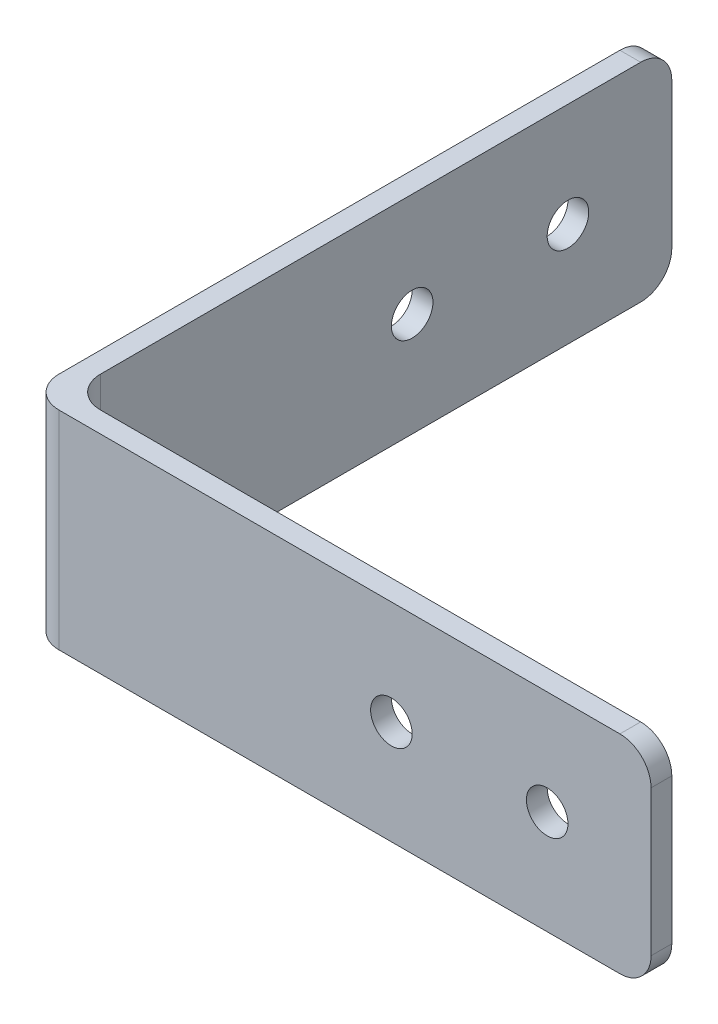
SolidWorks part; units mm, degrees
material "AISI 321 Annealed Stainless Steel (SS)"
ref_plane "Front Plane" through (0, 0, 0) normal (0, 0, 1) x (1, 0, 0)
ref_plane "Top Plane" through (0, 0, 0) normal (0, 1, 0) x (1, 0, 0)
ref_plane "Right Plane" through (0, 0, 0) normal (1, 0, 0) x (0, 0, -1)
sketch "Sketch1" plane through (0, 0, 0) normal (0, 1, 0) x (1, 0, 0)
  line L0 (-31.6449, 36.3551) -> (-31.6449, -21.6449)
  line L1 (-31.6449, -21.6449) -> (26.3551, -21.6449)
  line L2 (26.3551, -21.6449) -> (26.3551, -23.6449)
  line L3 (26.3551, -23.6449) -> (-33.6449, -23.6449)
  line L4 (-33.6449, -23.6449) -> (-33.6449, 36.3551)
  line L5 (-33.6449, 36.3551) -> (-31.6449, 36.3551)
  dimension "D1" = 60
  dimension "D2" = 60
  dimension "D3" = 58
  dimension "D4" = 58
  dimension "D5" = 2
extrude "Boss-Extrude1" add sketch "Sketch1" along normal blind 20
fillet "Fillet1" radius 3 6 edges at (-31.6449, 10, 21.6449) (-33.6449, 10, 23.6449) (26.3551, 20, 22.6449) (26.3551, 0, 22.6449) (-32.6449, 0, -36.3551) (-32.6449, 20, -36.3551)
sketch "Sketch3" plane through (0, 0, 21.6449) normal (0, 0, -1) x (-1, 0, 0)
  line L0 (-26.3551, 10) -> (28.6449, 10) construction
  line L1 (-26.3551, 17) -> (-26.3551, 3) construction
  line L2 (28.6449, 0) -> (28.6449, 20) construction
  circle A0 centre (-1.3551, 10) radius 2
  circle A1 centre (-16.3551, 10) radius 2
  dimension "D1" = 4
  dimension "D2" = 4
  dimension "D3" = 10
  dimension "D4" = 15
sketch "Sketch4" plane through (-31.6449, 0, 0) normal (1, 0, 0) x (0, 0, -1)
  line L0 (-18.6449, 10) -> (36.3551, 10) construction
  line L3 (36.3551, 17) -> (36.3551, 3) construction
  line L4 (-18.6449, 20) -> (-18.6449, 0) construction
  circle A0 centre (26.3551, 10) radius 2
  circle A1 centre (11.3551, 10) radius 2
  dimension "D1" = 4
  dimension "D2" = 4
  dimension "D3" = 10
  dimension "D4" = 15
extrude "Cut-Extrude1" cut sketch "Sketch3" against normal through all
extrude "Cut-Extrude2" cut sketch "Sketch4" against normal through all
